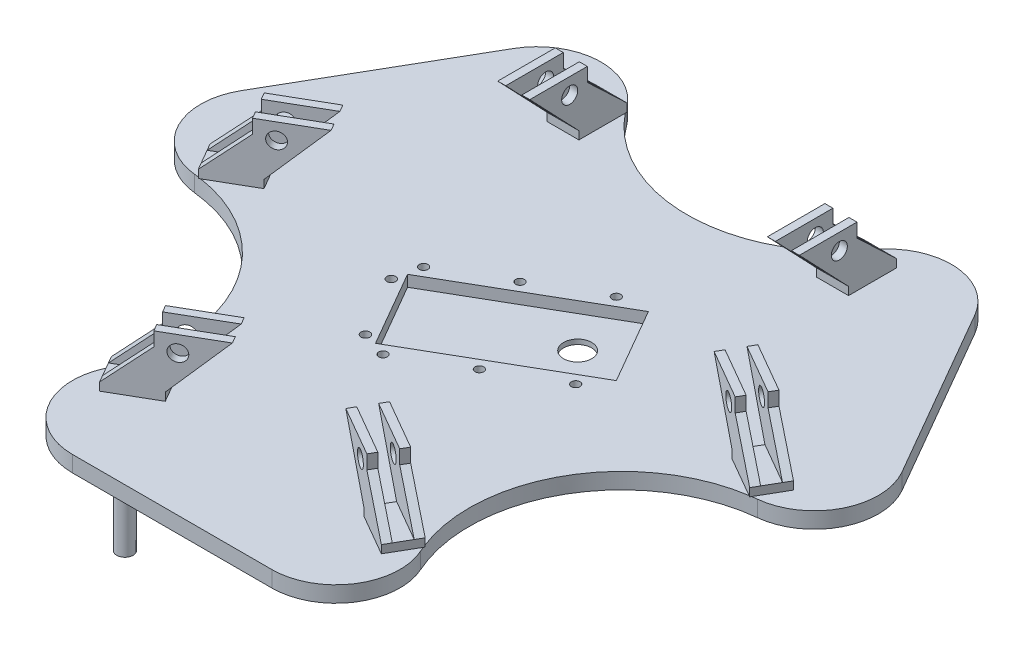
SolidWorks part; units mm, degrees
ref_plane "Front Plane" through (0, 0, 0) normal (0, 0, 1) x (1, 0, 0)
ref_plane "Top Plane" through (0, 0, 0) normal (0, 1, 0) x (1, 0, 0)
ref_plane "Right Plane" through (0, 0, 0) normal (1, 0, 0) x (0, 0, -1)
sketch "Sketch1" plane through (0, 0, 0) normal (0, 1, 0) x (1, 0, 0)
  line L0 (0, 303.1089) -> (0, 0) construction
  line L3 (-175, 0) -> (175, 0) construction
  line L5 (-87.5, 151.5544) -> (87.5, 151.5544) construction
  line L6 (0, 303.1089) -> (-175, 0) construction
  line L7 (0, 303.1089) -> (175, 0) construction
  line L8 (-71.9583, 178.4735) -> (-103.0417, 124.6354)
  line L9 (71.9583, 178.4735) -> (103.0417, 124.6354)
  line L10 (-31.0834, 0) -> (31.0834, 0)
  arc A1 (-38.4488, 180.2173) -> (38.4488, 180.2173) centre (0, 208.1089) ccw
  arc A2 (-49.3484, 28.1481) -> (-87.7972, 94.7434) centre (-92.7276, 47.5) ccw
  arc A3 (87.7972, 94.7434) -> (49.3484, 28.1481) centre (92.7276, 47.5) ccw
  arc A4 (103.0417, 124.6354) -> (87.7972, 94.7434) centre (85.7212, 114.6354) cw
  arc A5 (31.0834, 0) -> (49.3484, 28.1481) centre (31.0834, 20) ccw
  arc A6 (-31.0834, 0) -> (-49.3484, 28.1481) centre (-31.0834, 20) cw
  arc A7 (-103.0417, 124.6354) -> (-87.7972, 94.7434) centre (-85.7212, 114.6354) ccw
  arc A8 (-71.9583, 178.4735) -> (-38.4488, 180.2173) centre (-54.6378, 168.4735) cw
  arc A9 (71.9583, 178.4735) -> (38.4488, 180.2173) centre (54.6378, 168.4735) ccw
  point P15 (133.8638, 71.25)
  point P19 (92.7276, 0)
  point P24 (-92.7276, 0)
  point P27 (-133.8638, 71.25)
  point P30 (-41.1362, 231.8589)
  point P33 (41.1362, 231.8589)
  dimension "D3" = 95
  dimension "D4" = 95
  dimension "D5" = 95
  dimension "D6" = 20
  dimension "D7" = 20
  dimension "D8" = 20
  dimension "D9" = 20
  dimension "D10" = 20
  dimension "D1" = 350
  dimension "D2" = 350
extrude "Boss-Extrude1" add sketch "Sketch1" along normal blind 5
sketch "Sketch2" plane through (0, 0, 0) normal (0, 1, 0) x (1, 0, 0)
  line L1 (-71.9583, 178.4735) -> (-103.0417, 124.6354) construction
  line L2 (103.0417, 124.6354) -> (71.9583, 178.4735) construction
  line L3 (-31.0834, 0) -> (31.0834, 0) construction
  circle A0 centre (0, 208.1089) radius 47.5
  circle A1 centre (-92.7276, 47.5) radius 47.5
  circle A2 centre (92.7276, 47.5) radius 47.5
  dimension "D3" = 95
  dimension "D1" = 95
  dimension "D2" = 95
sketch "Sketch14" plane through (0, 0, 0) normal (0, -1, 0) x (1, 0, 0)
  line L0 (-31.0834, 0) -> (31.0834, 0) construction
  circle A0 centre (-1.4197, -7.5) radius 2.54
  circle A1 centre (-22.2257, -7.5) radius 2.54
  circle A2 centre (26.7743, -7.5) radius 2.54
  circle A3 centre (-16.6597, -58.3) radius 2.54
  circle A4 centre (31.589, -59.3469) radius 2.54
  circle A5 centre (-22.2257, -65.5) radius 2.54
  dimension "D7" = 5.08
  dimension "D8" = 5.08
  dimension "D9" = 5.08
  dimension "D10" = 5.08
  dimension "D11" = 5.08
  dimension "D12" = 5.08
  dimension "D1" = 28.194
  dimension "D2" = 49
  dimension "D3" = 50.8
  dimension "D4" = 15.24
  dimension "D5" = 48.26
  dimension "D6" = 58
  dimension "D13" = 52.07
  dimension "D14" = 7.5
  dimension "D15" = 5.566
extrude "Boss-Extrude5" add sketch "Sketch14" along normal blind 3.81
hole_wizard "1/8 (0.125) Diameter Hole3" positions "Sketch15" profile "Sketch16" hole size "1/8" standard "ANSI Inch"
sketch "Sketch15" plane through (0, -3.81, 0) normal (0, -1, 0) x (-1, 0, 0)
  point P0 (22.2257, 7.5)
  point P3 (1.4197, 7.5)
  point P6 (-26.7743, 7.5)
  point P9 (-31.589, 59.3469)
  point P12 (16.6597, 58.3)
  point P15 (22.2257, 65.5)
sketch "Sketch16" plane through (-22.2257, -3.81, -7.5) normal (1, 0, 0) x (0, 0, -1)
  line L0 (0, 0) -> (0, 4.7629)
  line L1 (0, 4.7629) -> (1.5875, 3.809)
  line L2 (1.5875, 3.809) -> (1.5875, 0)
  line L5 (1.5875, 0) -> (0, 0)
  line L10 (0, 4.7629) -> (-1.5875, 3.809) construction
  line L11 (0, -6.35) -> (0, 107.95) construction
  dimension "Hole Dia." = 3.175
  dimension "Hole Depth" = 3.809
  dimension "Drill Angle" = 118
sketch "Sketch17" plane through (0, -3.81, 0) normal (0, -1, 0) x (1, 0, 0)
  circle A0 centre (-22.2257, -65.5) radius 2.54
  circle A1 centre (-22.2257, -7.5) radius 2.54
extrude "Boss-Extrude6" add sketch "Sketch17" along normal blind 16.51
hole_wizard "1/8 (0.125) Diameter Hole4" positions "Sketch18" profile "Sketch19" hole size "1/8" standard "ANSI Inch"
sketch "Sketch18" plane through (0, -20.32, 0) normal (0, -1, 0) x (-1, 0, 0)
  point P0 (22.2257, 7.5)
  point P3 (22.2257, 65.5)
sketch "Sketch19" plane through (-22.2257, -20.32, -7.5) normal (1, 0, 0) x (0, 0, -1)
  line L0 (0, 0) -> (0, 21.2729)
  line L1 (0, 21.2729) -> (1.5875, 20.319)
  line L2 (1.5875, 20.319) -> (1.5875, 0)
  line L5 (1.5875, 0) -> (0, 0)
  line L10 (0, 21.2729) -> (-1.5875, 20.319) construction
  line L11 (0, -6.35) -> (0, 107.95) construction
  dimension "Hole Dia." = 3.175
  dimension "Hole Depth" = 20.319
  dimension "Drill Angle" = 118
sketch "Sketch25" plane through (0, 5, 0) normal (0, 1, 0) x (1, 0, 0)
  line L0 (-92.7276, 47.5) -> (87.5, 151.5544) construction
  line L1 (103.0417, 124.6354) -> (71.9583, 178.4735) construction
  line L2 (0, 208.1089) -> (0, 0) construction
  line L3 (-31.0834, 0) -> (31.0834, 0) construction
  line L4 (92.7276, 47.5) -> (-87.5, 151.5544) construction
  line L5 (-71.9583, 178.4735) -> (-103.0417, 124.6354) construction
sketch "Sketch26" plane through (0, 5, 0) normal (0, 1, 0) x (1, 0, 0)
  line L1 (0, 208.1089) -> (0, 0) construction
  line L3 (92.7276, 47.5) -> (-87.5, 151.5544) construction
  point P0 (0, 101.0363)
sketch "Sketch27" plane through (0, 5, 0) normal (0, 1, 0) x (1, 0, 0)
  line L0 (-91.0069, 102.8291) -> (-86.0069, 94.1689)
  line L1 (-86.0069, 94.1689) -> (-73.0165, 101.6689)
  line L2 (-73.0165, 101.6689) -> (-78.0165, 110.3291)
  line L3 (-78.0165, 110.3291) -> (-91.0069, 102.8291)
  line L5 (-75.5165, 105.999) -> (-88.5069, 98.499) construction
  line L6 (-92.7276, 47.5) -> (87.5, 151.5544) construction
  dimension "D1" = 10
  dimension "D2" = 15
  dimension "D3" = 42.0561
extrude "Boss-Extrude11" add sketch "Sketch27" along normal blind 2.5
sketch "Sketch28" plane through (-62.278, 0, -107.8687) normal (0.5, 0, 0.866) x (0.866, 0, -0.5)
  line L0 (-27.3997, 7.5) -> (-15.0267, 19.2174)
  line L1 (-15.0267, 19.2174) -> (-15.0267, 23.5585)
  line L2 (-15.0267, 23.5585) -> (2.9274, 23.5585)
  line L3 (2.9274, 23.5585) -> (-12.3997, 7.5)
  line L4 (-12.3997, 7.5) -> (-27.3997, 7.5)
extrude "Boss-Extrude12" add sketch "Sketch28" against normal blind 2.5
ref_plane "Plane2" through (-64.778, 0, -112.1989) normal (0.5, 0, 0.866) x (0.866, 0, -0.5)
ref_plane "Plane3" through (-43.75, 0, -75.7772) normal (0.5, 0, 0.866) x (0.866, 0, -0.5)
sketch "Sketch29" plane through (-63.528, 0, -110.0338) normal (-0.5, 0, -0.866) x (-0.866, 0, 0.5)
  line L0 (-2.9274, 23.5585) -> (15.0267, 23.5585) construction
  line L1 (15.0267, 23.5585) -> (15.0267, 19.2174) construction
  circle A0 centre (9.5267, 18.5585) radius 2.5
  dimension "D1" = 5
  dimension "D2" = 5.5
extrude "Cut-Extrude1" cut sketch "Sketch29" against normal through all both and the other way through all
mirror "Mirror4" about plane through (-64.778, 0, -112.1989) normal (0.5, 0, 0.866) of "Boss-Extrude12", "Cut-Extrude1"
mirror "Mirror5" about plane through (-43.75, 0, -75.7772) normal (0.5, 0, 0.866) of "Boss-Extrude11", "Mirror4", "Boss-Extrude12", "Cut-Extrude1"
mirror "Mirror6" about plane through (0, 0, 0) normal (1, 0, 0) of "Boss-Extrude11", "Mirror5", "Boss-Extrude12", "Mirror4"
mirror "Mirror7" about plane through (-43.75, 0, -75.7772) normal (0.5, 0, 0.866) of "Mirror6", "Mirror4", "Mirror5"
sketch "Sketch30" plane through (0, 5, 0) normal (0, 1, 0) x (1, 0, 0)
  line L0 (87.5, 151.5544) -> (-20.3202, 89.3044)
  line L1 (20.1403, 128.4273) -> (33.7915, 104.7828)
  line L2 (103.0417, 124.6354) -> (71.9583, 178.4735) construction
  line L6 (20.1403, 128.4273) -> (-27.4922, 100.9267)
  line L7 (-27.4922, 100.9267) -> (-13.841, 77.2822)
  line L9 (33.7915, 104.7828) -> (-13.841, 77.2822)
  line L11 (33.245, 104.9292) -> (26.2445, 117.0546) construction
  line L12 (26.2445, 117.0546) -> (22.3195, 123.8529) construction
  line L13 (19.9939, 127.8809) -> (-26.9457, 100.7803) construction
  line L14 (-26.9457, 100.7803) -> (-13.6946, 77.8286) construction
  line L15 (30.8202, 103.5292) -> (-10.6635, 79.5786) construction
  line L16 (30.8202, 103.5292) -> (33.245, 104.9292) construction
  line L17 (22.3195, 123.8529) -> (19.9939, 127.8809) construction
  line L18 (-10.6635, 79.5786) -> (-13.6946, 77.8286) construction
  dimension "D1" = 124.5
  dimension "D2" = 55.0012
  dimension "D3" = 0.4
  dimension "D4" = 0.4
  dimension "D5" = 0.4
  dimension "D6" = 0.4
extrude "Cut-Extrude2" cut sketch "Sketch30" against normal blind 3.5
sketch "Sketch31" plane through (0, 1.5, 0) normal (0, 1, 0) x (1, 0, 0)
  line L0 (-27.4922, 100.9267) -> (-13.841, 77.2822) construction
  line L1 (33.7915, 104.7828) -> (-13.841, 77.2822) construction
  line L2 (20.1403, 128.4273) -> (33.7915, 104.7828) construction
  line L3 (20.1403, 128.4273) -> (33.7915, 104.7828) construction
  line L4 (26.9659, 116.6051) -> (-20.6666, 89.1044) construction
  line L5 (-27.4922, 100.9267) -> (-13.841, 77.2822) construction
  line L6 (33.7915, 104.7828) -> (-13.841, 77.2822) construction
  line L7 (9.9752, 91.0325) -> (-3.6759, 114.677) construction
  line L8 (20.1403, 128.4273) -> (-27.4922, 100.9267) construction
  circle A0 centre (-9.8413, 95.3544) radius 4 construction
  circle A1 centre (-9.8413, 95.3544) radius 4.4 construction
  circle A2 centre (16.1406, 110.3551) radius 4.4
  dimension "D1" = 12.5
extrude "Cut-Extrude3" cut sketch "Sketch31" against normal through all
sketch "Sketch33" plane through (0, 5, 0) normal (0, 1, 0) x (1, 0, 0)
  line L0 (-3.6759, 114.677) -> (15.6001, 81.2899) construction
  line L1 (20.1403, 128.4273) -> (-27.4922, 100.9267) construction
  line L2 (20.1403, 128.4273) -> (-27.4922, 100.9267) construction
  circle A0 centre (11.1307, 127.43) radius 1.35
  circle A2 centre (-7.9219, 116.43) radius 1.35
  circle A12 centre (-26.9744, 105.43) radius 1.35
  circle A13 centre (-28.7597, 97.1246) radius 1.385
  circle A14 centre (-17.7597, 78.0721) radius 1.385
  circle A15 centre (-9.6744, 75.4655) radius 1.35
  circle A16 centre (9.3781, 86.4655) radius 1.35
  circle A17 centre (28.4307, 97.4655) radius 1.35
extrude "Cut-Extrude4" cut sketch "Sketch33" against normal through all
sketch "Sketch34" plane through (0, 5, 0) normal (0, 1, 0) x (1, 0, 0)
  line L0 (0, 0) -> (0, 160.6089)
  line L1 (-31.0834, 0) -> (31.0834, 0) construction
  line L2 (-87.5, 151.5544) -> (51.5914, 71.25)
  line L3 (-71.9583, 178.4735) -> (-103.0417, 124.6354) construction
  arc A0 (-37.0561, 178.3919) -> (37.0561, 178.3919) centre (0, 208.1089) ccw construction
  arc A1 (85.52, 94.45) -> (48.4639, 30.267) centre (92.7276, 47.5) ccw construction
ref_plane "Plane4" through (43.75, 0, -75.7772) normal (-0.5, 0, 0.866) x (0.866, 0, 0.5)
ref_plane "Plane5" through (0, 0, 0) normal (1, 0, 0) x (0, 0, -1)
equation "\"D2@Sketch1\"=\"D1@Sketch1\""
equation "\"D3@Sketch2\"=\"D1@Sketch2\""
equation "\"D2@Sketch2\"=\"D1@Sketch2\""
equation "\"D8@Sketch14\"=\"D7@Sketch14\""
equation "\"D9@Sketch14\"=\"D7@Sketch14\""
equation "\"D10@Sketch14\"=\"D7@Sketch14\""
equation "\"D11@Sketch14\"=\"D7@Sketch14\""
equation "\"D12@Sketch14\"=\"D7@Sketch14\""
equation "\"D7@Sketch1\"=\"D6@Sketch1\""
equation "\"D8@Sketch1\"=\"D7@Sketch1\""
equation "\"D9@Sketch1\"=\"D6@Sketch1\""
equation "\"D10@Sketch1\"=\"D8@Sketch1\""
